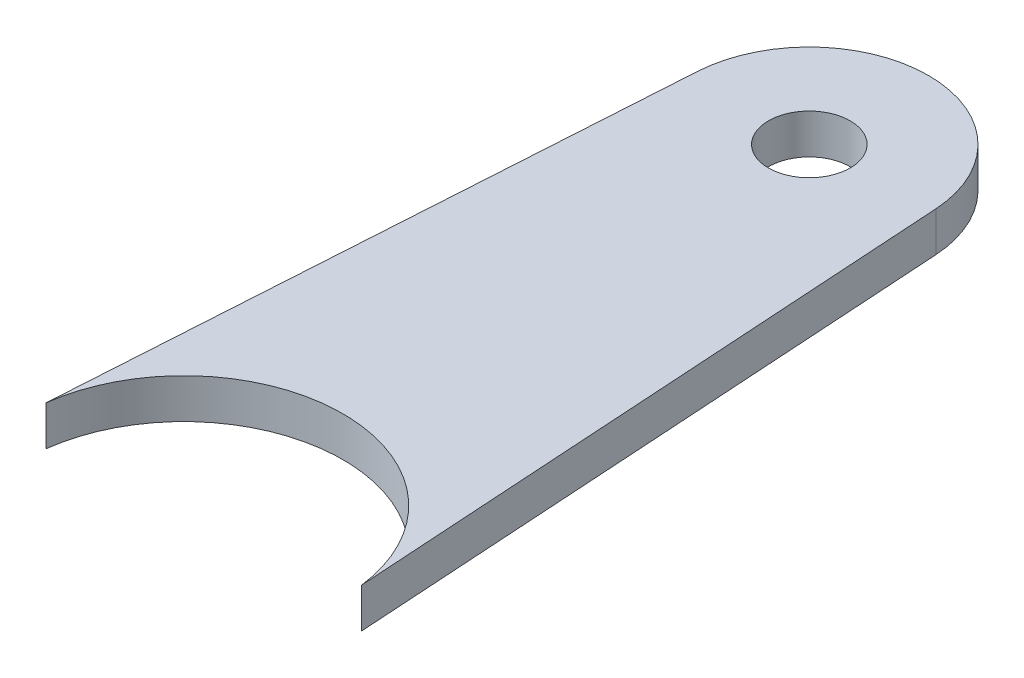
SolidWorks part; units mm, degrees
ref_plane "Front Plane" through (0, 0, 0) normal (0, 0, 1) x (1, 0, 0)
ref_plane "Top Plane" through (0, 0, 0) normal (0, 1, 0) x (1, 0, 0)
ref_plane "Right Plane" through (0, 0, 0) normal (1, 0, 0) x (0, 0, -1)
sketch "Sketch1" plane through (0, 0, 0) normal (0, 1, 0) x (1, 0, 0)
  line L0 (0, 0) -> (3.194, 50.5372)
  line L1 (0, 0) -> (25.4, 0)
  line L2 (25.4, 0) -> (22.206, 50.5372)
  arc A1 (3.194, 50.5372) -> (22.206, 50.5372) centre (12.7, 49.9364) cw
  circle A2 centre (12.7, 49.9364) radius 3.2639
  circle A3 centre (12.7, 0) radius 12.7
  point P9 (12.7, 0)
  dimension "D1" = 6.5278
  dimension "D2" = 49.9364
  dimension "D3" = 9.525
  dimension "D5" = 25.4
  dimension "D4" = 25.4
extrude "Boss-Extrude1" add sketch "Sketch1" along normal blind 3.175 contours A3 L2 A1 L0 A2
